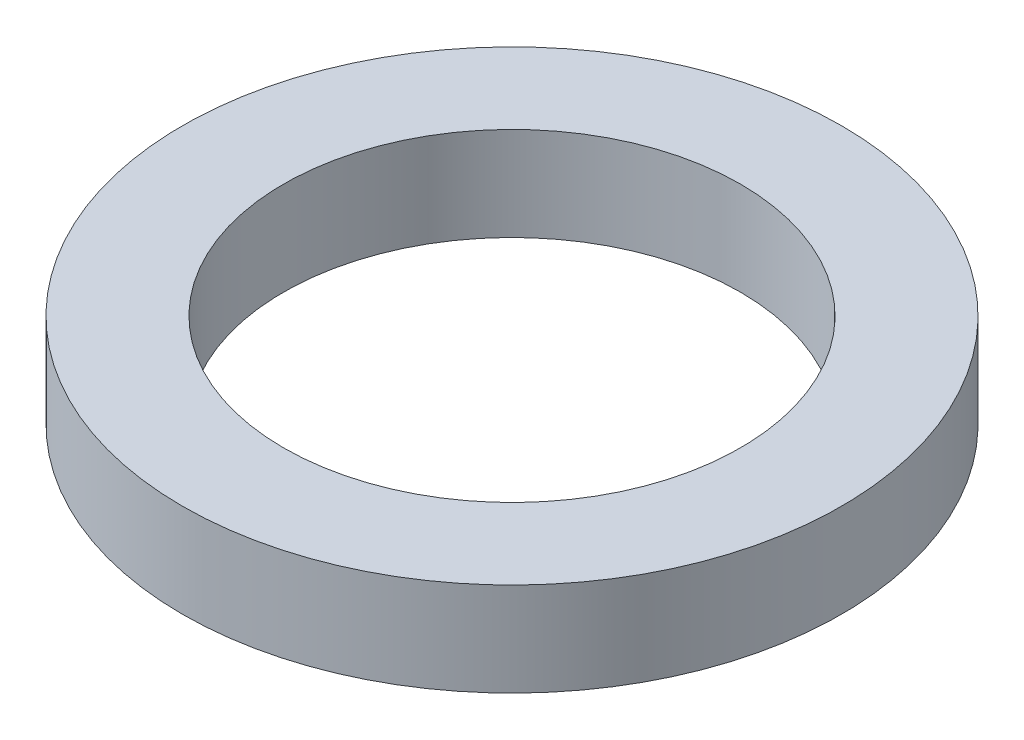
SolidWorks part; units mm, degrees
material "Plywood"
ref_plane "Front Plane" through (0, 0, 0) normal (0, 0, 1) x (1, 0, 0)
ref_plane "Top Plane" through (0, 0, 0) normal (0, 1, 0) x (1, 0, 0)
ref_plane "Right Plane" through (0, 0, 0) normal (1, 0, 0) x (0, 0, -1)
sketch "Sketch1" plane through (0, 0, 0) normal (0, 1, 0) x (1, 0, 0)
  circle A0 centre (0, 0) radius 44.7167
  dimension "D1" = 89.4334
extrude "Boss-Extrude1" add sketch "Sketch1" along normal blind 12.7
sketch "Sketch3" plane through (0, 0, 0) normal (0, 1, 0) x (1, 0, 0)
  circle A0 centre (0, 0) radius 31
  dimension "D1" = 62
extrude "Cut-Extrude1" cut sketch "Sketch3" along normal up to next
